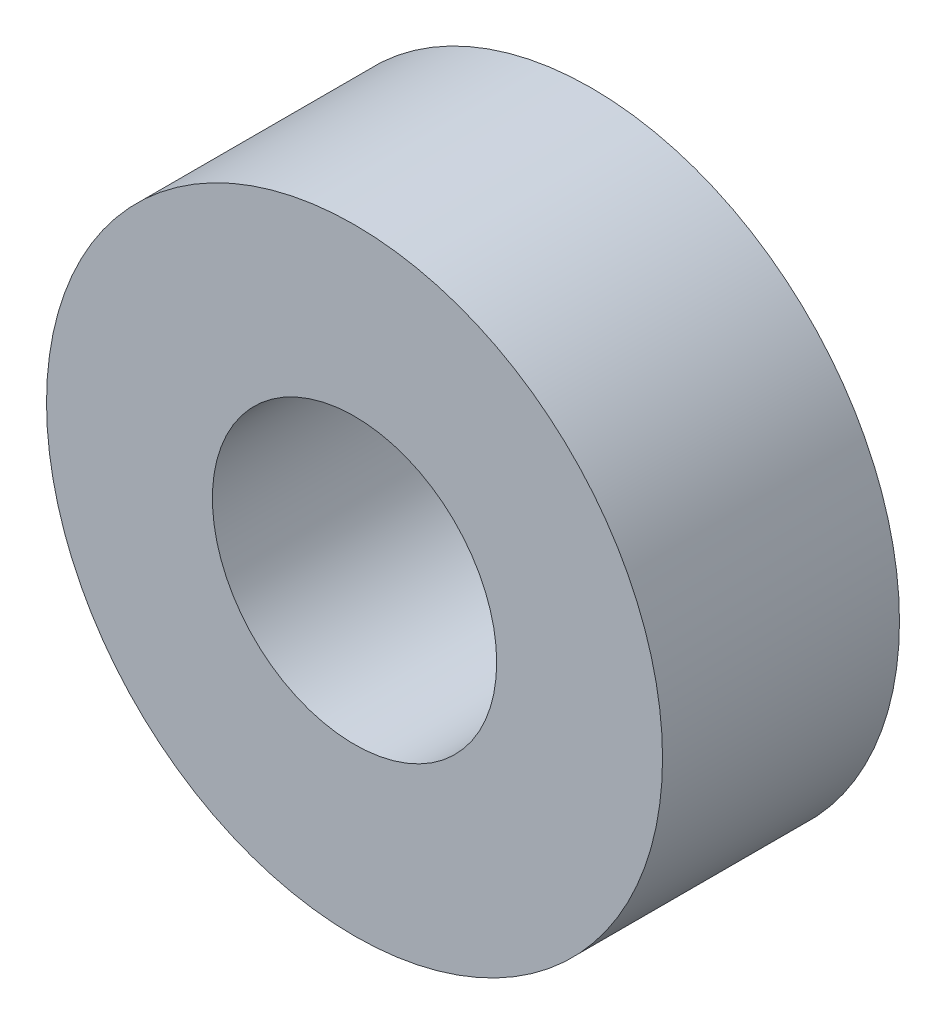
SolidWorks part; units mm, degrees
ref_plane "Front Plane" through (0, 0, 0) normal (0, 0, 1) x (1, 0, 0)
ref_plane "Top Plane" through (0, 0, 0) normal (0, 1, 0) x (1, 0, 0)
ref_plane "Right Plane" through (0, 0, 0) normal (1, 0, 0) x (0, 0, -1)
sketch "Sketch1" plane through (0, 0, 0) normal (0, 0, 1) x (1, 0, 0)
  circle A0 centre (0, 0) radius 6.5
extrude "Boss-Extrude1" add sketch "Sketch1" along normal blind 5
sketch "Sketch3" plane through (0, 0, 5) normal (0, 0, 1) x (1, 0, 0)
  circle A0 centre (0, 0) radius 3
extrude "Cut-Extrude1" cut sketch "Sketch3" against normal through all
